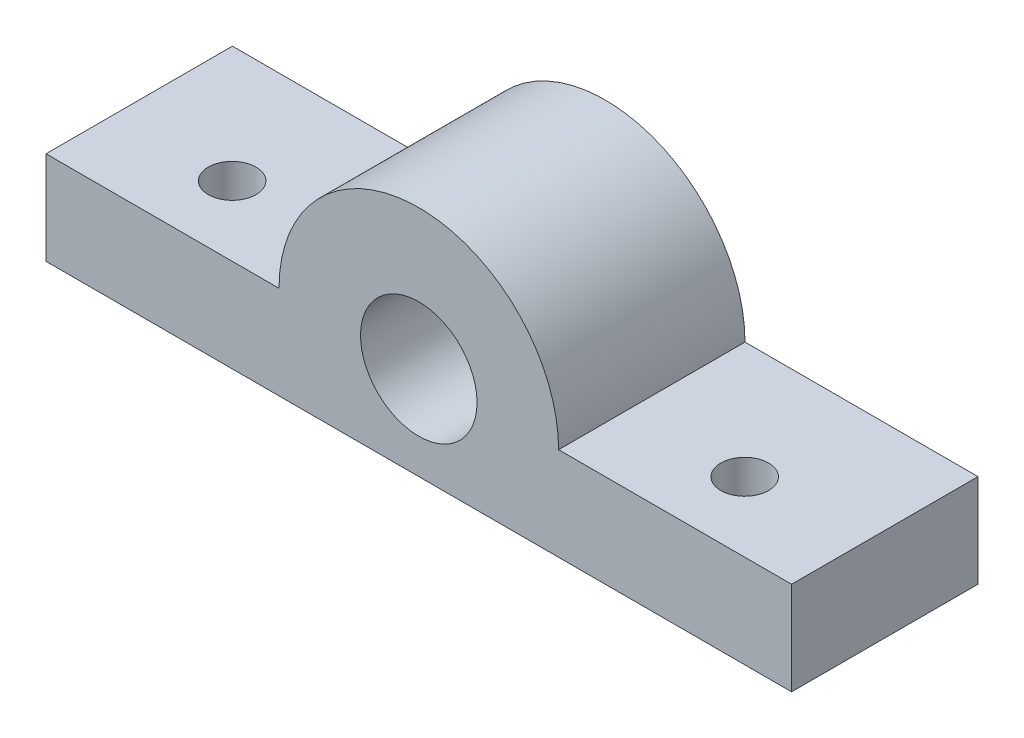
SolidWorks part; units mm, degrees
material "Hierro dúctil"
ref_plane "Alzado" through (0, 0, 0) normal (0, 0, 1) x (1, 0, 0)
ref_plane "Planta" through (0, 0, 0) normal (0, 1, 0) x (1, 0, 0)
ref_plane "Vista lateral" through (0, 0, 0) normal (1, 0, 0) x (0, 0, -1)
sketch "Croquis1" plane through (0, 0, 0) normal (0, 0, 1) x (1, 0, 0)
  line L0 (-51.9416, 0) -> (-19.9416, 0)
  line L1 (-19.9416, 0) -> (-19.9416, 4)
  line L2 (-19.9416, 4) -> (-29.9416, 4)
  line L3 (-51.9416, 0) -> (-51.9416, 4)
  line L4 (-51.9416, 4) -> (-41.9416, 4)
  arc A0 (-41.9416, 4) -> (-29.9416, 4) centre (-35.9416, 4) cw
  circle A1 centre (-35.9416, 4) radius 2.5
  dimension "D3" = 5
  dimension "D1" = 32
  dimension "D2" = 4
  dimension "D4" = 10
extrude "Saliente-Extruir1" add sketch "Croquis1" along normal blind 8
sketch "Croquis2" plane through (0, 4, 0) normal (0, 1, 0) x (1, 0, 0)
  line L0 (-51.9416, -4) -> (-19.9416, -4) construction
  line L1 (-51.9416, -8) -> (-51.9416, 0) construction
  line L2 (-19.9416, -8) -> (-19.9416, 0) construction
  line L3 (-46.9416, 0) -> (-46.9416, -8) construction
  line L4 (-41.9416, 0) -> (-51.9416, 0) construction
  line L5 (-41.9416, -8) -> (-51.9416, -8) construction
  line L6 (-24.9416, 0) -> (-24.9416, -8) construction
  line L7 (-19.9416, 0) -> (-29.9416, 0) construction
  line L8 (-19.9416, -8) -> (-29.9416, -8) construction
hole_wizard "Perforador para roscar para macho de roscar para M2.5x0.451" positions "Croquis3" profile "Croquis4" hole size "M2.5x0.45" standard "Ansi Metric"
sketch "Croquis3" plane through (0, 4, 0) normal (0, 1, 0) x (1, 0, 0)
  point P0 (-46.9401, -5.0126)
  point P2 (-24.9415, -5.0126)
sketch "Croquis4" plane through (-46.9401, 4, 5.0126) normal (1, 0, 0) x (0, 0, 1)
  line L0 (0, 0) -> (0, 10.6159)
  line L1 (0, 10.6159) -> (1.025, 10)
  line L2 (1.025, 10) -> (1.025, 0)
  line L5 (1.025, 0) -> (0, 0)
  line L10 (0, 10.6159) -> (-1.025, 10) construction
  line L11 (0, -6.35) -> (0, 107.95) construction
  dimension "Diámetro de taladro" = 2.05
  dimension "Profundidad de taladro" = 10
  dimension "Ángulo de perforador" = 118
